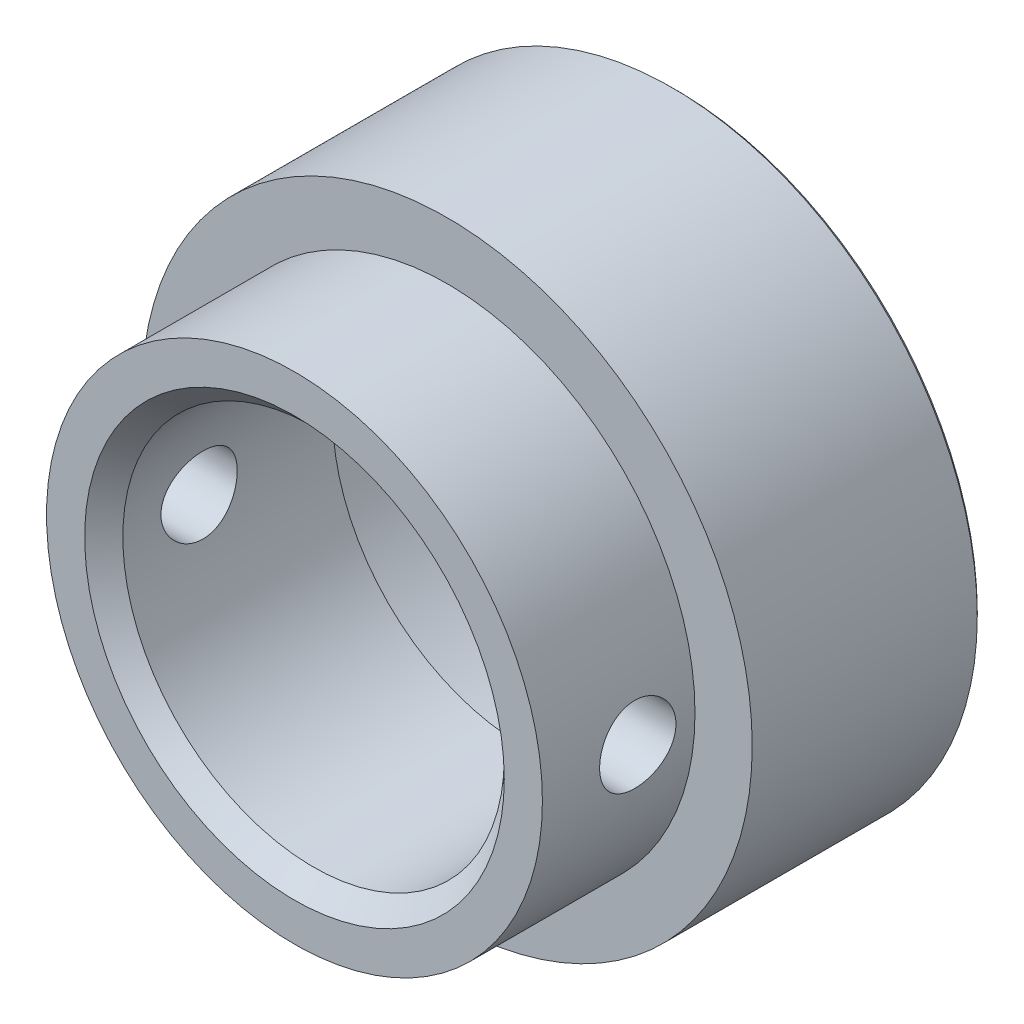
SolidWorks part; units mm, degrees
ref_plane "Спереди" through (0, 0, 0) normal (0, 0, 1) x (1, 0, 0)
ref_plane "Сверху" through (0, 0, 0) normal (0, 1, 0) x (1, 0, 0)
ref_plane "Справа" through (0, 0, 0) normal (1, 0, 0) x (0, 0, -1)
sketch "Эскиз1" plane through (0, 0, 0) normal (0, 0, 1) x (1, 0, 0)
  circle A0 centre (0, 0) radius 80
  dimension "D1" = 160
extrude "Бобышка-Вытянуть1" add sketch "Эскиз1" along normal blind 60
sketch "Эскиз2" plane through (0, 0, 60) normal (0, 0, 1) x (1, 0, 0)
  circle A0 centre (0, 0) radius 65
  dimension "D1" = 130
extrude "Бобышка-Вытянуть2" add sketch "Эскиз2" along normal blind 40
sketch "Эскиз3" plane through (0, 0, 0) normal (0, 0, -1) x (-1, 0, 0)
  circle A0 centre (0, 0) radius 70
  dimension "D1" = 140
extrude "Вырез-Вытянуть1" cut sketch "Эскиз3" against normal blind 40
sketch "Эскиз4" plane through (0, 0, 100) normal (0, 0, 1) x (1, 0, 0)
  circle A0 centre (0, 0) radius 50
  dimension "D1" = 100
extrude "Вырез-Вытянуть2" cut sketch "Эскиз4" against normal through all
chamfer "Фаска1" distance 1 angle 45 2 edges at (80, 0, 0) (-70, 0, 0)
sketch "Эскиз5" plane through (0, 0, 0) normal (1, 0, 0) x (0, 0, -1)
  line L0 (-100, 0) -> (57.5106, 0) construction
  line L1 (-100, 65) -> (-100, -65) construction
  circle A0 centre (-75, 0) radius 10
  dimension "D2" = 20
  dimension "D1" = 25
extrude "Вырез-Вытянуть3" cut sketch "Эскиз5" against normal through all and the other way through all
chamfer "Фаска2" distance 5 angle 45 1 edges at (50, 0, 100)
